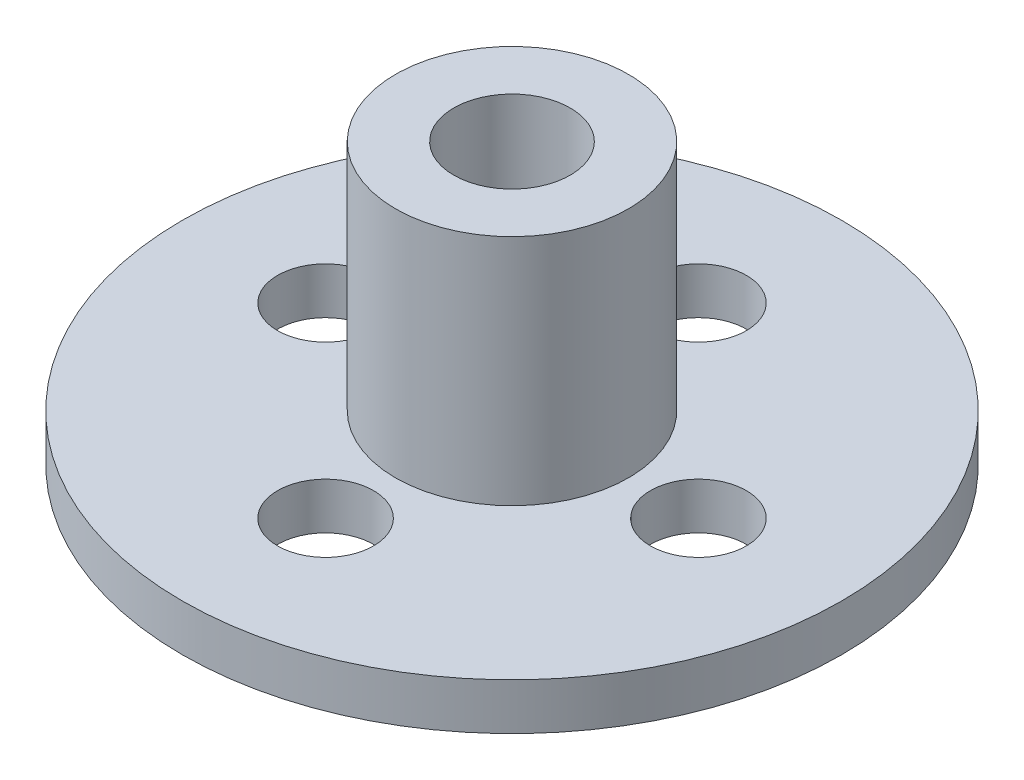
SolidWorks part; units mm, degrees
ref_plane "前视基准面" through (0, 0, 0) normal (0, 0, 1) x (1, 0, 0)
ref_plane "上视基准面" through (0, 0, 0) normal (0, 1, 0) x (1, 0, 0)
ref_plane "右视基准面" through (0, 0, 0) normal (1, 0, 0) x (0, 0, -1)
other "Configuration Table"
sketch "草图1" plane through (0, 0, 0) normal (0, 1, 0) x (1, 0, 0)
  circle A0 centre (0, 0) radius 14.1493
  circle A1 centre (0, 8) radius 2.0581
  circle A2 centre (-8, 0) radius 2.0581
  circle A3 centre (0, -8) radius 2.0581
  circle A4 centre (8, 0) radius 2.0581
  dimension "D1" = 16
  dimension "D2" = 16
  dimension "D3" = 8
  dimension "D4" = 8
extrude "凸台-拉伸1" add sketch "草图1" along normal blind 2
sketch "草图2" plane through (0, 2, 0) normal (0, 1, 0) x (1, 0, 0)
  circle A0 centre (0, 0) radius 5
  circle A1 centre (0, 0) radius 2.5
extrude "凸台-拉伸2" add sketch "草图2" along normal blind 10
